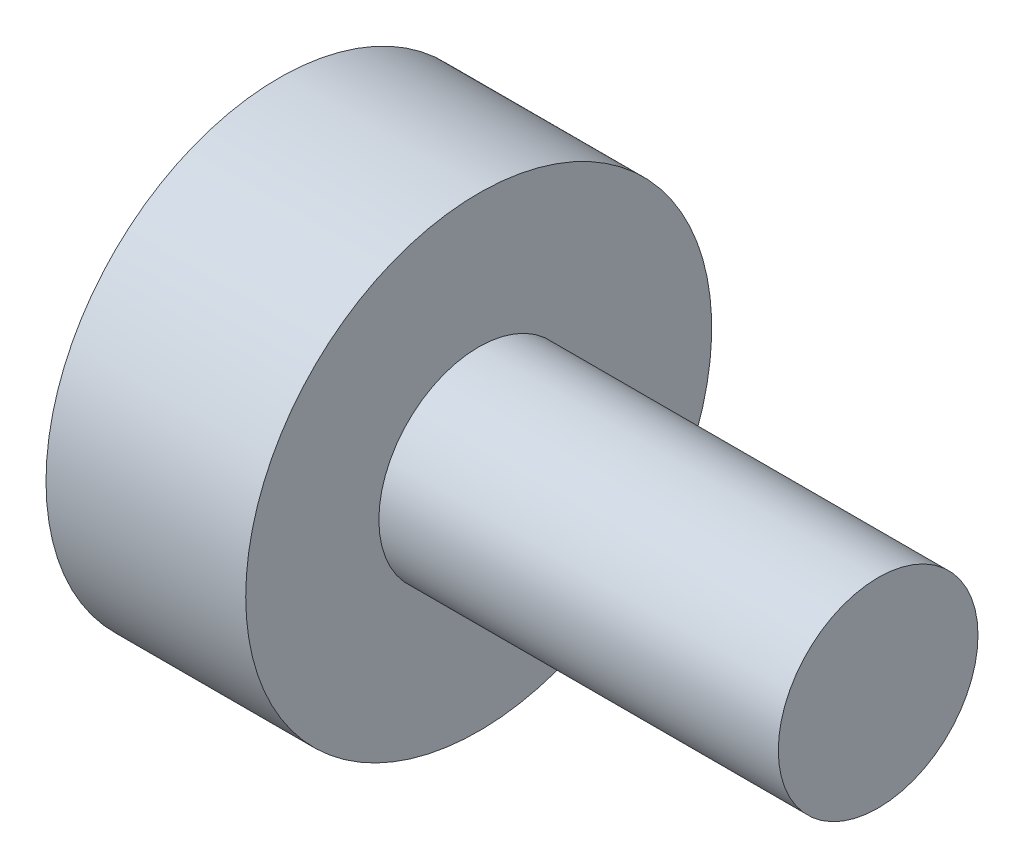
SolidWorks part; units mm, degrees
ref_plane "Спереди" through (0, 0, 0) normal (0, 0, 1) x (1, 0, 0)
ref_plane "Сверху" through (0, 0, 0) normal (0, 1, 0) x (1, 0, 0)
ref_plane "Справа" through (0, 0, 0) normal (1, 0, 0) x (0, 0, -1)
sketch "Эскиз1" plane through (0, 0, 0) normal (0, 0, 1) x (1, 0, 0)
  line L0 (0, 0) -> (100, 0)
  line L1 (0, 0) -> (0, 20)
  line L2 (0, 20) -> (10, 20)
  line L3 (10, 20) -> (10, 35)
  line L4 (10, 35) -> (40, 35)
  line L5 (40, 35) -> (40, 15)
  line L6 (40, 15) -> (100, 15)
  line L7 (100, 0) -> (100, 15)
revolve "Повернуть1" add sketch "Эскиз1" angle 360 about L0
ref_plane "Плоскость4" through (0, 0, 0) normal (1, 0, 0) x (0, 0, -1)
sketch "Эскиз2" plane through (0, 0, 0) normal (1, 0, 0) x (0, 0, -1)
  circle A0 centre (0, 0) radius 5
extrude "Вырез-Вытянуть1" cut sketch "Эскиз2" along normal blind 20
